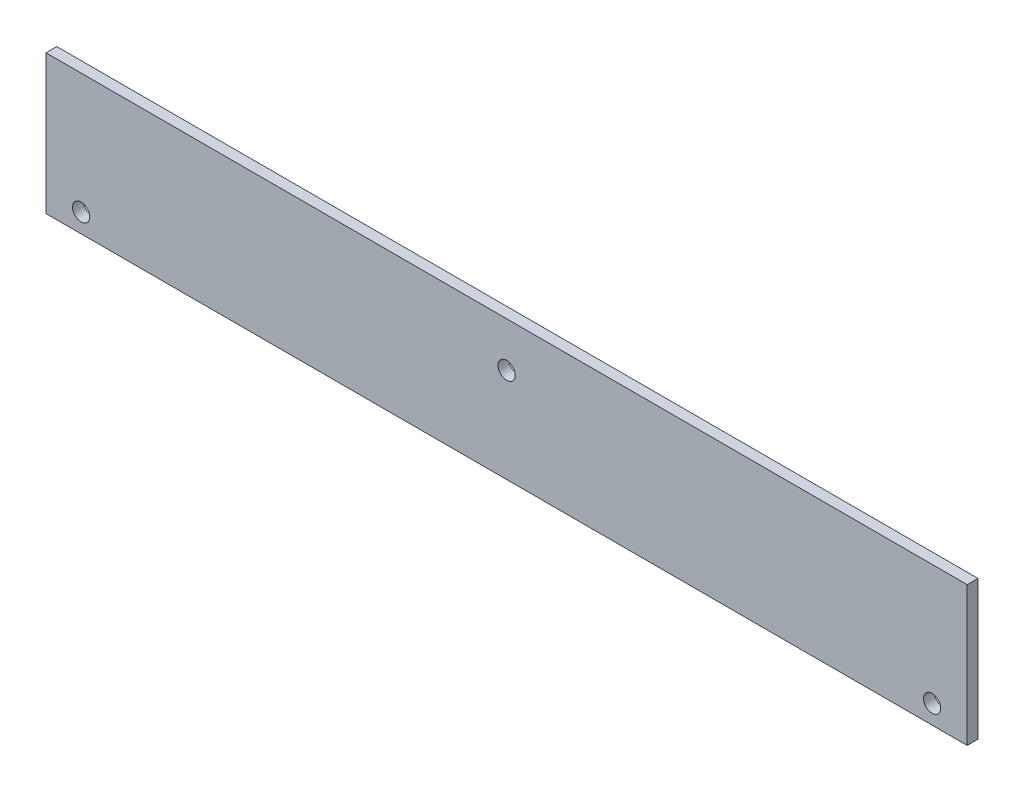
SolidWorks part; units mm, degrees
ref_plane "Front Plane" through (0, 0, 0) normal (0, 0, 1) x (1, 0, 0)
ref_plane "Top Plane" through (0, 0, 0) normal (0, 1, 0) x (1, 0, 0)
ref_plane "Right Plane" through (0, 0, 0) normal (1, 0, 0) x (0, 0, -1)
sketch "Sketch1" plane through (0, 0, 0) normal (0, 0, 1) x (1, 0, 0)
  line L0 (-85.25, 27.8868) -> (85.25, 27.8868)
  line L1 (85.25, 27.8868) -> (85.25, 2.1132)
  line L5 (-85.25, 2.1132) -> (-85.25, 27.8868)
  line L6 (-85.25, 2.1132) -> (85.25, 2.1132)
extrude "Boss-Extrude1" add sketch "Sketch1" along normal blind 2
sketch "Sketch2" plane through (0, 0, 2) normal (0, 0, 1) x (1, 0, 0)
  line L0 (0, 27.8868) -> (0, 2.1132) construction
  line L4 (-85.25, 2.1132) -> (85.25, 2.1132) construction
  line L5 (85.25, 2.1132) -> (85.25, 27.8868) construction
  line L6 (85.25, 27.8868) -> (-85.25, 27.8868) construction
  line L9 (-78.75, 5.6168) -> (0, 19.6168) construction
  line L10 (0, 19.6168) -> (78.75, 5.6168) construction
  circle A0 centre (-78.75, 5.6168) radius 1.6
  circle A1 centre (78.75, 5.6168) radius 1.6
  circle A6 centre (0, 19.6168) radius 1.6
  dimension "D1" = 3.2
  dimension "D2" = 3.2
  dimension "D3" = 8.27
  dimension "D4" = 6.5
  dimension "D5" = 22.27
  dimension "D6" = 3.2
  dimension "D7" = 22.27
extrude "Cut-Extrude1" cut sketch "Sketch2" against normal blind 18
